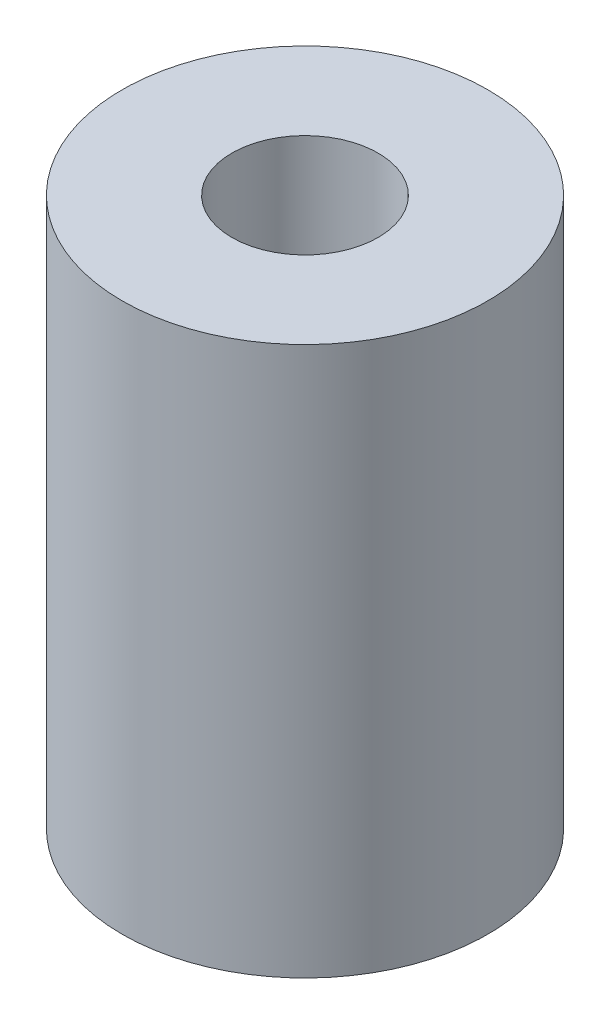
SolidWorks part; units mm, degrees
material "ASTM A36 Steel"
ref_plane "Front" through (0, 0, 0) normal (0, 0, 1) x (1, 0, 0)
ref_plane "Top" through (0, 0, 0) normal (0, 1, 0) x (1, 0, 0)
ref_plane "Right" through (0, 0, 0) normal (1, 0, 0) x (0, 0, -1)
sketch "Sketch2" plane through (0, 0, 0) normal (0, 1, 0) x (1, 0, 0)
  circle A0 centre (0, 0) radius 7.9375
  circle A1 centre (0, 0) radius 3.175
  dimension "D1" = 15.875
  dimension "D2" = 6.35
extrude "Boss-Extrude1" add sketch "Sketch2" along normal blind 23.8125
